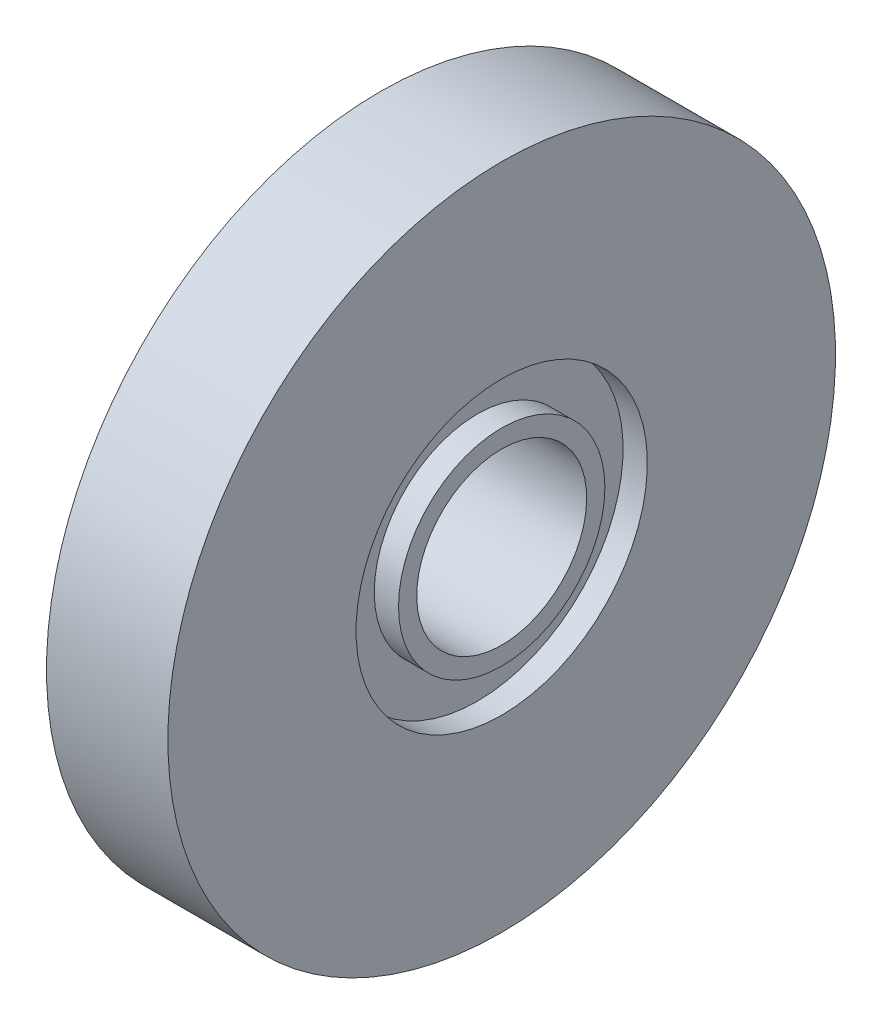
SolidWorks part; units mm, degrees
ref_plane "Front Plane" through (0, 0, 0) normal (0, 0, 1) x (1, 0, 0)
ref_plane "Top Plane" through (0, 0, 0) normal (0, 1, 0) x (1, 0, 0)
ref_plane "Right Plane" through (0, 0, 0) normal (1, 0, 0) x (0, 0, -1)
sketch "Sketch1" plane through (0, 0, 0) normal (0, 0, 1) x (1, 0, 0)
  line L0 (0, 0) -> (-17.6107, 0) construction
  line L1 (-5, 7) -> (5, 7)
  line L2 (5, 7) -> (5, 8.5)
  line L3 (5, 8.5) -> (3, 8.5)
  line L4 (3, 8.5) -> (3, 12)
  line L5 (3, 12) -> (5, 12)
  line L6 (5, 12) -> (5, 27.5)
  line L7 (5, 27.5) -> (-5, 27.5)
  line L8 (-5, 27.5) -> (-5, 12)
  line L9 (-5, 8.5) -> (-3, 8.5)
  line L10 (-3, 8.5) -> (-3, 12)
  line L11 (-3, 12) -> (-5, 12)
  line L12 (-5, 8.5) -> (-5, 7)
  point P5 (0, 7)
  point P11 (0, 27.5)
  dimension "D1" = 14
  dimension "D2" = 17
  dimension "D3" = 24
  dimension "D4" = 55
  dimension "D5" = 2
  dimension "D6" = 2
  dimension "D7" = 10
revolve "Revolve1" add sketch "Sketch1" angle 360 about L0
